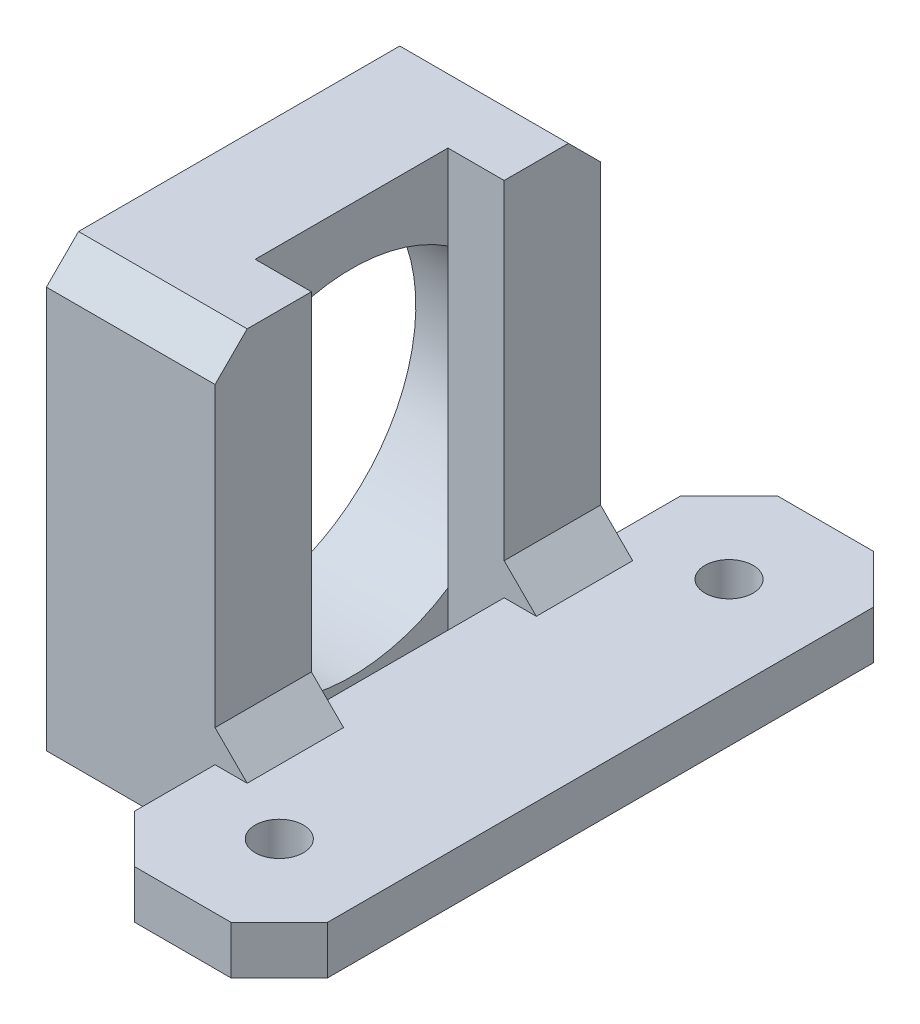
SolidWorks part; units mm, degrees
ref_plane "Front Plane" through (0, 0, 0) normal (0, 0, 1) x (1, 0, 0)
ref_plane "Top Plane" through (0, 0, 0) normal (0, 1, 0) x (1, 0, 0)
ref_plane "Right Plane" through (0, 0, 0) normal (1, 0, 0) x (0, 0, -1)
sketch "Sketch1" plane through (0, 0, 0) normal (0, 1, 0) x (1, 0, 0)
  line L0 (-6, 17) -> (-3, 20)
  line L1 (-3, 20) -> (3, 20)
  line L2 (-6, 17) -> (-6, -17)
  line L3 (-3, -20) -> (3, -20)
  line L4 (6, 17) -> (6, -17)
  line L5 (-6, 20) -> (6, -20) construction
  line L6 (-6, -20) -> (6, 20) construction
  line L7 (3, 20) -> (6, 17)
  line L8 (-6, -17) -> (-3, -20)
  line L9 (3, -20) -> (6, -17)
  circle A0 centre (0, 14) radius 1.5
  circle A1 centre (0, -14) radius 1.5
  point P0 (0, 0)
  dimension "D3" = 3
  dimension "D1" = 40
  dimension "D2" = 12
  dimension "D4" = 28
  dimension "D9" = 14
extrude "Boss-Extrude1" add sketch "Sketch1" along normal blind 3 contours A0 | L2 L8 L3 L9 L4 L7 L1 L0 | A1
sketch "Sketch2" plane through (0, 3, 0) normal (0, 1, 0) x (1, 0, 0)
  line L1 (-9.5, 12) -> (-6, 12)
  line L2 (-9.5, 12) -> (-9.5, 6)
  line L3 (-9.5, 6) -> (-6, 6)
  line L4 (-6, 12) -> (-6, 6)
  line L5 (-3, -20) -> (3, -20) construction
  line L6 (-9.5, -6) -> (-6, -6)
  line L7 (-9.5, -6) -> (-9.5, -12)
  line L8 (-9.5, -12) -> (-6, -12)
  line L9 (-6, -6) -> (-6, -12)
  line L10 (-3, 20) -> (3, 20) construction
  line L11 (-6, 17) -> (-6, -17) construction
  dimension "D1" = 6
  dimension "D2" = 6
  dimension "D3" = 8
  dimension "D4" = 8
  dimension "D5" = 3.5
  dimension "D6" = 3.5
extrude "Boss-Extrude2" add sketch "Sketch2" against normal blind 29 from offset 22.5 contours L2 L1 L4 L3 | L9 L8 L7 L6
chamfer "Chamfer2" distance 2 4 edges at (-6, 0, -9) (-6, 0, 9) (-6, 3, -9) (-6, 3, 9)
sketch "Sketch3" plane through (-9.5, 0, 0) normal (-1, 0, 0) x (0, 0, 1)
  line L1 (-12, 25.5) -> (12, 25.5)
  line L2 (-12, 25.5) -> (-12, -3.5)
  line L3 (-12, -3.5) -> (12, -3.5)
  line L4 (12, 25.5) -> (12, -3.5)
  circle A0 centre (0, 11) radius 11
  point P9 (0, 25.5)
  point P11 (-12, 11)
  dimension "D1" = 22
extrude "Boss-Extrude4" add sketch "Sketch3" along normal blind 7
chamfer "Chamfer3" distance 2 angle 45 4 edges at (-11.25, -3.5, -12) (-11.25, -3.5, 12) (-11.25, 25.5, 12) (-11.25, 25.5, -12)
